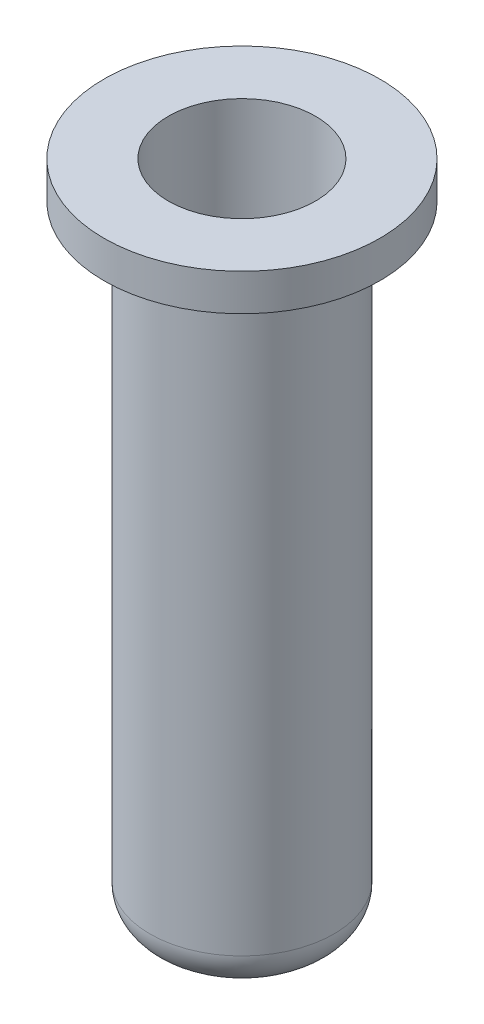
SolidWorks part; units mm, degrees
ref_plane "Front Plane" through (0, 0, 0) normal (0, 0, 1) x (1, 0, 0)
ref_plane "Top Plane" through (0, 0, 0) normal (0, 1, 0) x (1, 0, 0)
ref_plane "Right Plane" through (0, 0, 0) normal (1, 0, 0) x (0, 0, -1)
sketch "Sketch2" plane through (0, 0, 0) normal (0, 1, 0) x (1, 0, 0)
  circle A0 centre (0, 0) radius 2.5
  dimension "D1" = 5
extrude "Boss-Extrude1" add sketch "Sketch2" along normal blind 18
fillet "Fillet3" radius 1 1 edges at (0, 0, 2.5)
sketch "Sketch5" plane through (0, 18, 0) normal (0, 1, 0) x (1, 0, 0)
  circle A0 centre (0, 0) radius 3.75
  circle A1 centre (0, 0) radius 2.5 construction
  circle A2 centre (0, 0) radius 2.5
  dimension "D1" = 7.5
extrude "Boss-Extrude2" add sketch "Sketch5" against normal blind 1
hole_wizard "Ø1.0mm Dowel Hole1" positions "Sketch6" profile "Sketch7" hole size "Ø1.0" standard "ANSI Metric"
sketch "Sketch6" plane through (0, 18, 0) normal (0, 1, 0) x (1, 0, 0)
  point P0 (0, 0)
sketch "Sketch7" plane through (0, 18, 0) normal (1, 0, 0) x (0, 0, 1)
  line L0 (0, 0) -> (0, 17.25)
  line L1 (0, 17.25) -> (2, 13.7859)
  line L2 (2, 13.7859) -> (2, 0)
  line L5 (2, 0) -> (0, 0)
  line L10 (0, 17.25) -> (-2, 13.7859) construction
  line L11 (0, -6.35) -> (0, 107.95) construction
  dimension "Hole Dia." = 4
  dimension "Hole Depth" = 17.25
  dimension "Drill Angle" = 60
